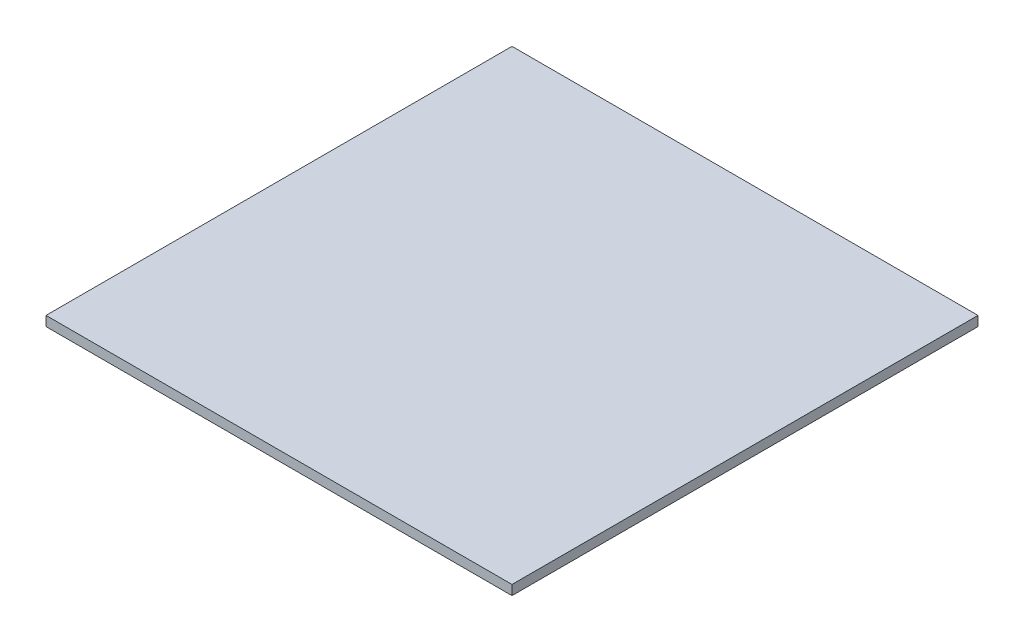
SolidWorks part; units mm, degrees
ref_plane "Front Plane" through (0, 0, 0) normal (0, 0, 1) x (1, 0, 0)
ref_plane "Top Plane" through (0, 0, 0) normal (0, 1, 0) x (1, 0, 0)
ref_plane "Right Plane" through (0, 0, 0) normal (1, 0, 0) x (0, 0, -1)
sketch "Sketch1" plane through (0, 0, 0) normal (0, 1, 0) x (1, 0, 0)
  line L1 (-116.0162, 124.5973) -> (188.7838, 124.5973)
  line L2 (-116.0162, 124.5973) -> (-116.0162, -180.2027)
  line L3 (-116.0162, -180.2027) -> (188.7838, -180.2027)
  line L4 (188.7838, 124.5973) -> (188.7838, -180.2027)
  dimension "D1" = 304.8
  dimension "D2" = 304.8
extrude "Boss-Extrude1" add sketch "Sketch1" along normal blind 6.35
